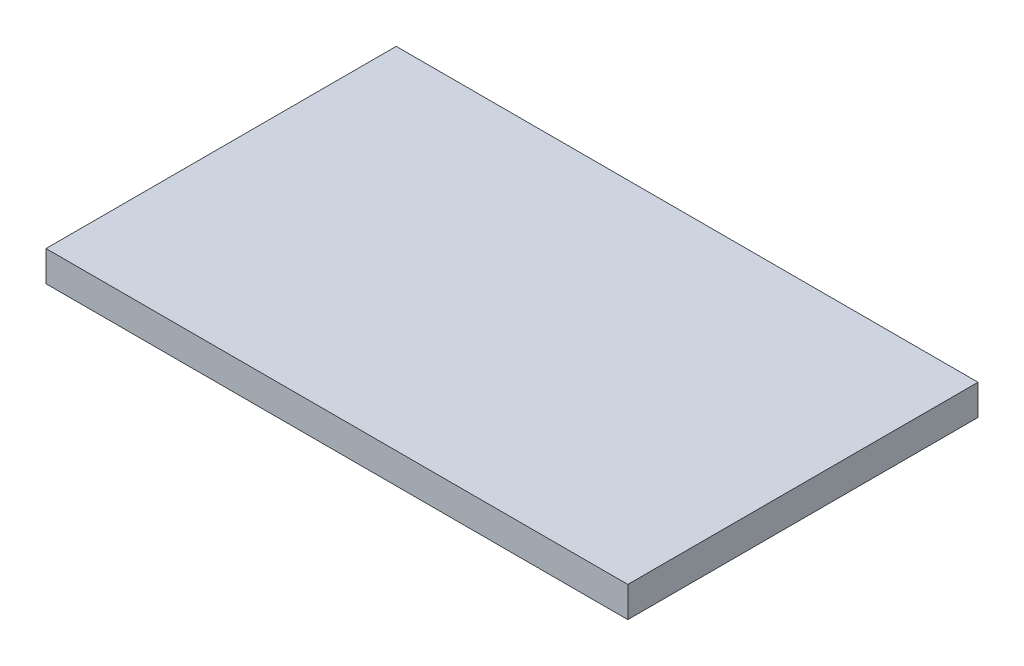
SolidWorks part; units mm, degrees
ref_plane "Front Plane" through (0, 0, 0) normal (0, 0, 1) x (1, 0, 0)
ref_plane "Top Plane" through (0, 0, 0) normal (0, 1, 0) x (1, 0, 0)
ref_plane "Right Plane" through (0, 0, 0) normal (1, 0, 0) x (0, 0, -1)
sketch "Sketch1" plane through (0, 0, 0) normal (0, 1, 0) x (1, 0, 0)
  line L1 (95.3262, -57.3783) -> (-95.3262, -57.3783)
  line L2 (95.3262, -57.3783) -> (95.3262, 57.3783)
  line L3 (95.3262, 57.3783) -> (-95.3262, 57.3783)
  line L4 (-95.3262, -57.3783) -> (-95.3262, 57.3783)
  line L5 (95.3262, -57.3783) -> (-95.3262, 57.3783) construction
  line L6 (95.3262, 57.3783) -> (-95.3262, -57.3783) construction
  point P0 (0, 0)
extrude "Boss-Extrude1" add sketch "Sketch1" along normal blind 10
sketch "Sketch2" plane through (0, 10, 0) normal (0, 1, 0) x (1, 0, 0)
  point P0 (-46.9637, -26.4974)
  line B0 (-49.0905, -19.3478) -> (-61.6051, -19.7848)
  line B1 (-60.5262, -29.1762) -> (-49.5116, -28.7916)
sketch_block_instance "VGA-Cutout-1"
sketch_block "VGA-Cutout"
sketch_block_instance "VGA-Cutout-2"
